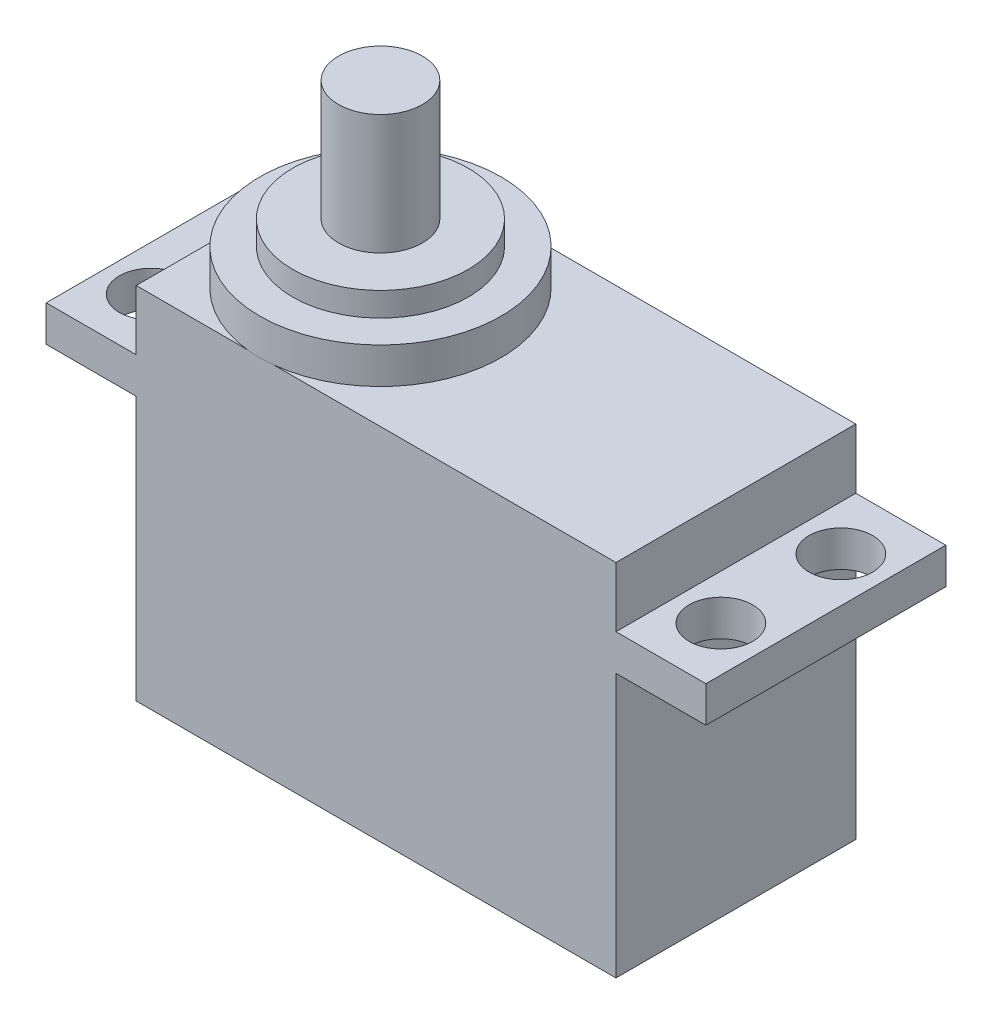
SolidWorks part; units mm, degrees
ref_plane "Ön Düzlem" through (0, 0, 0) normal (0, 0, 1) x (1, 0, 0)
ref_plane "Üst Düzlem" through (0, 0, 0) normal (0, 1, 0) x (1, 0, 0)
ref_plane "Sağ Düzlem" through (0, 0, 0) normal (1, 0, 0) x (0, 0, -1)
sketch "Çizim1" plane through (0, 0, 0) normal (0, 1, 0) x (1, 0, 0)
  line L1 (-20, -10) -> (20, -10)
  line L2 (-20, -10) -> (-20, 10)
  line L3 (-20, 10) -> (20, 10)
  line L4 (20, -10) -> (20, 10)
  line L5 (-20, -10) -> (20, 10) construction
  line L6 (-20, 10) -> (20, -10) construction
  point P0 (0, 0)
  dimension "D1" = 40
  dimension "D2" = 20
extrude "Yükseklik-Ekstrüzyon1" add sketch "Çizim1" along normal blind 30
ref_plane "Düzlem1" through (0, 22, 0) normal (0, 1, 0) x (1, 0, 0)
sketch "Çizim2" plane through (0, 22, 0) normal (0, 1, 0) x (1, 0, 0)
  line L1 (-27.5, -10) -> (27.5, -10)
  line L2 (-27.5, -10) -> (-27.5, 10)
  line L3 (-27.5, 10) -> (27.5, 10)
  line L4 (27.5, -10) -> (27.5, 10)
  line L5 (-27.5, -10) -> (27.5, 10) construction
  line L6 (-27.5, 10) -> (27.5, -10) construction
  point P0 (0, 0)
  dimension "D1" = 20
  dimension "D2" = 55
extrude "Yükseklik-Ekstrüzyon2" add sketch "Çizim2" along normal blind 3
sketch "Çizim3" plane through (0, 25, 0) normal (0, 1, 0) x (1, 0, 0)
  line L0 (-35.0664, 0) -> (37.9485, 0) construction
  line L1 (0, 16.743) -> (0, -19.5246) construction
  circle A0 centre (-23.75, 5.0017) radius 2.647
  circle A1 centre (-23.75, -5.0017) radius 2.647
  circle A2 centre (23.75, -5.0017) radius 2.647
  circle A3 centre (23.75, 5.0017) radius 2.647
extrude "Kes-Ekstrüzyon1" cut sketch "Çizim3" against normal blind 13
sketch "Çizim4" plane through (0, 30, 0) normal (0, 1, 0) x (1, 0, 0)
  circle A0 centre (-9.6316, 0) radius 10.0604
extrude "Yükseklik-Ekstrüzyon3" add sketch "Çizim4" along normal blind 3
sketch "Çizim5" plane through (0, 33, 0) normal (0, 1, 0) x (1, 0, 0)
  circle A0 centre (-9.6316, 0) radius 7.3177
extrude "Yükseklik-Ekstrüzyon4" add sketch "Çizim5" along normal blind 2
sketch "Çizim6" plane through (0, 35, 0) normal (0, 1, 0) x (1, 0, 0)
  circle A0 centre (-9.6316, 0) radius 3.5
  dimension "D1" = 7
extrude "Yükseklik-Ekstrüzyon5" add sketch "Çizim6" along normal blind 10
